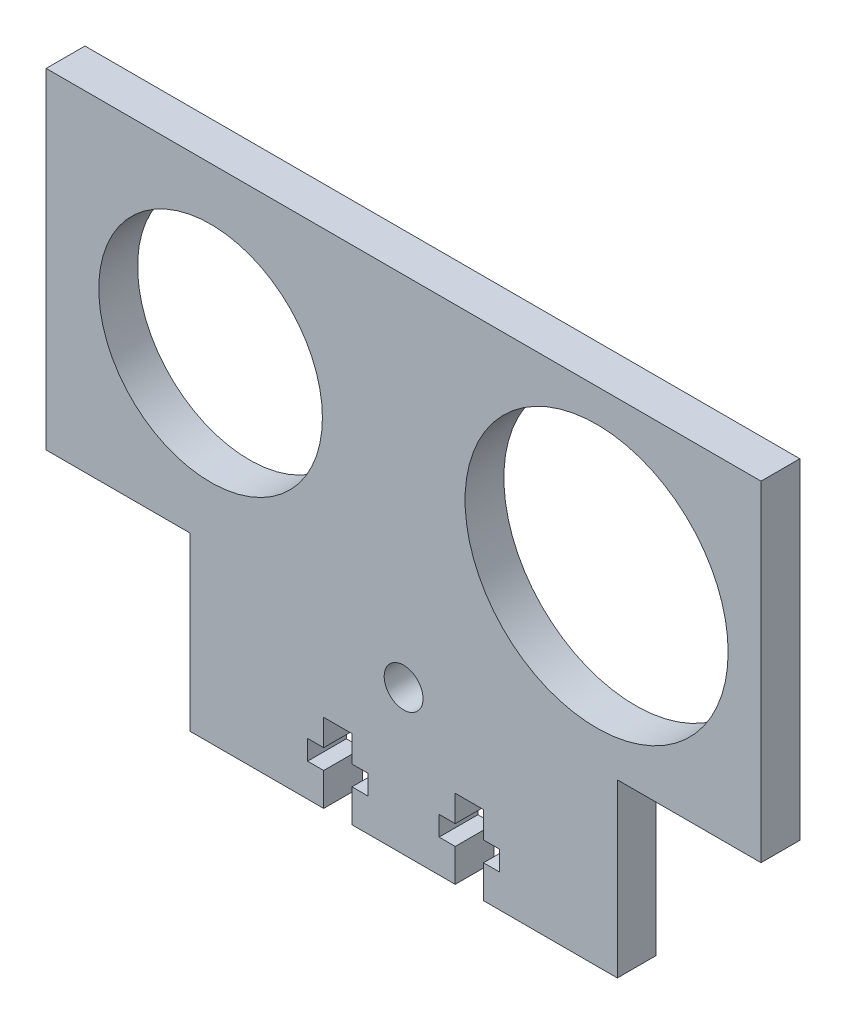
SolidWorks part; units mm, degrees
ref_plane "Front Plane" through (0, 0, 0) normal (0, 0, 1) x (1, 0, 0)
ref_plane "Top Plane" through (0, 0, 0) normal (0, 1, 0) x (1, 0, 0)
ref_plane "Right Plane" through (0, 0, 0) normal (1, 0, 0) x (0, 0, -1)
sketch "Sketch1" plane through (0, 0, 0) normal (0, 0, 1) x (1, 0, 0)
  line L0 (0, 0) -> (-29.3449, 29.3449) construction
  line L1 (0, 0) -> (0, 54.3449) construction
  line L2 (-32.5, 4.1) -> (-32.5, -22)
  line L3 (-32.5, -22) -> (32.5, -22)
  line L4 (32.5, 4.1) -> (54.3449, 4.1)
  line L5 (0, 0) -> (0, -22) construction
  line L6 (54.3449, 4.1) -> (54.3449, 54.3449)
  line L7 (0, 0) -> (29.3449, 29.3449) construction
  line L10 (-32.5, 4.1) -> (-54.3449, 4.1)
  line L11 (-54.3449, 4.1) -> (-54.3449, 54.3449)
  line L12 (-54.3449, 54.3449) -> (54.3449, 54.3449)
  line L13 (32.5, 4.1) -> (32.5, -22)
  circle A0 centre (0, 0) radius 2.95
  circle A1 centre (-29.3449, 29.3449) radius 17
  circle A2 centre (29.3449, 29.3449) radius 20
  point P16 (0, 54.3449)
  dimension "D1" = 5.9
  dimension "D9" = 34
  dimension "D10" = 40
  dimension "D2" = 41.5
  dimension "D4" = 45
  dimension "D5" = 22
  dimension "D6" = 65
  dimension "D7" = 26.1
  dimension "D8" = 25
  dimension "D3" = 25
  dimension "D11" = 45
extrude "Boss-Extrude1" add sketch "Sketch1" along normal blind 5.9
sketch "Sketch3" plane through (0, 0, 5.9) normal (0, 0, 1) x (1, 0, 0)
  line L0 (-32.5, -22) -> (32.5, -22) construction
  line L1 (-12.15, -22) -> (-7.85, -22)
  line L2 (-12.15, -22) -> (-12.15, -17)
  line L3 (-12.15, -10) -> (-7.85, -10)
  line L4 (-7.85, -22) -> (-7.85, -17)
  line L5 (0, 0) -> (0, -22) construction
  line L6 (-7.85, -14) -> (-5.4, -14)
  line L7 (-14.6, -14) -> (-12.15, -14)
  line L8 (-14.6, -14) -> (-14.6, -17)
  line L9 (-14.6, -17) -> (-12.15, -17)
  line L10 (-5.4, -14) -> (-5.4, -17)
  line L11 (-12.15, -14) -> (-12.15, -10)
  line L12 (-7.85, -17) -> (-5.4, -17)
  line L13 (-7.85, -14) -> (-7.85, -10)
  line L14 (7.85, -14) -> (7.85, -10)
  line L15 (7.85, -17) -> (5.4, -17)
  line L16 (12.15, -14) -> (12.15, -10)
  line L17 (5.4, -14) -> (5.4, -17)
  line L18 (14.6, -17) -> (12.15, -17)
  line L19 (14.6, -14) -> (14.6, -17)
  line L20 (14.6, -14) -> (12.15, -14)
  line L21 (7.85, -14) -> (5.4, -14)
  line L22 (7.85, -22) -> (7.85, -17)
  line L23 (12.15, -10) -> (7.85, -10)
  line L24 (12.15, -22) -> (12.15, -17)
  line L25 (12.15, -22) -> (7.85, -22)
  point P6 (-10, -10)
  point P18 (-13.375, -17)
  dimension "D1" = 4.3
  dimension "D2" = 10
  dimension "D3" = 12
  dimension "D4" = 9.2
  dimension "D5" = 3
  dimension "D6" = 5
extrude "Cut-Extrude2" cut sketch "Sketch3" against normal through all
equation "\"smallPulleyTeeth\"= 15"
equation "\"largePulleyTeeth\"= 30"
equation "\"eighthThick\"= 2.9mm"
equation "\"sixteenthThick\"= 1.7mm"
equation "\"quarterThick\"=5.9mm"
equation "\"OD\"= 145mm"
equation "\"puckAngle\"= 60.5deg"
equation "\"puckDiam\"= 76.5mm"
equation "\"axlePress\"= 5.9mm"
equation "\"D1@Sketch1\"=\"axlePress\""
equation "\"D1@Boss-Extrude1\"=\"quarterThick\""
equation "\"press\"= 0.2mm"
equation "\"wheelClear\"= 0.3mm"
equation "\"10-32clear\"= 4.5mm"
equation "\"D1@Sketch3\"=\"10-32clear\" - \"press\""
equation "\"6-32clear\"= 3.3mm"
equation "\"8-32clear\"= 4.0mm"
equation "\"wheelHeight\"= 22mm"
equation "\"D5@Sketch1\"=\"wheelHeight\""
equation "\"D7@Sketch1\"=\"eighthThick\"*9"
equation "\"4-40clear\"= 2.55mm"
equation "\"wheelWell\"= 65mm"
equation "\"D6@Sketch1\"=\"wheelWell\""
